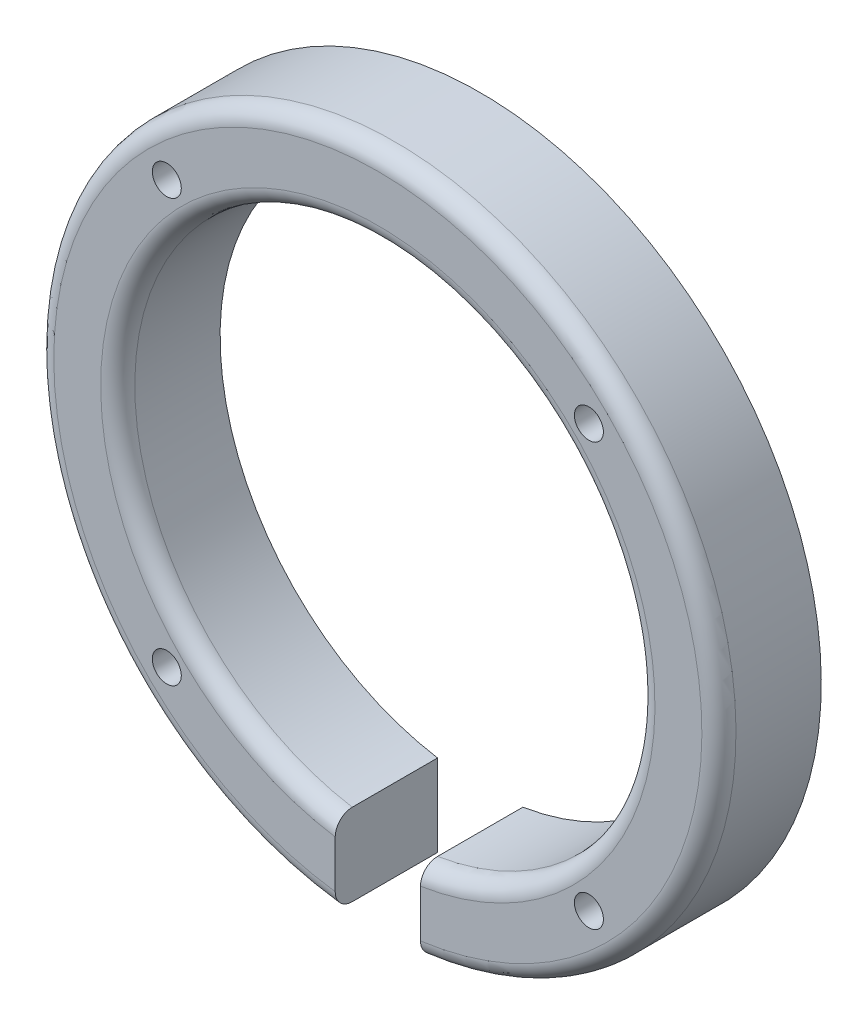
SolidWorks part; units mm, degrees
material "ABS"
ref_plane "前视基准面" through (0, 0, 0) normal (0, 0, 1) x (1, 0, 0)
ref_plane "上视基准面" through (0, 0, 0) normal (0, 1, 0) x (1, 0, 0)
ref_plane "右视基准面" through (0, 0, 0) normal (1, 0, 0) x (0, 0, -1)
sketch "草图1" plane through (0, 0, 0) normal (0, 0, 1) x (1, 0, 0)
  circle A0 centre (0, 0) radius 30.5
  circle A1 centre (0, 0) radius 40
  dimension "D1" = 61
  dimension "D2" = 80
extrude "凸台-拉伸1" add sketch "草图1" along normal blind 12
sketch "草图2" plane through (0, 0, 12) normal (0, 0, 1) x (1, 0, 0)
  line L0 (-28.2056, -28.2056) -> (28.3619, 28.3619) construction
  line L1 (0, 0) -> (0, 40) construction
  circle A1 centre (24.7487, 24.7487) radius 1.7
  circle A2 centre (24.7487, -24.7487) radius 1.7
  circle A3 centre (-24.7487, -24.7487) radius 1.7
  circle A4 centre (-24.7487, 24.7487) radius 1.7
  point P2 (26.6359, 22.7052)
  point P3 (0, 0)
  point P9 (0, 0)
  point P11 (24.5963, 24.9002)
  point P19 (0, 0)
  dimension "D2" = 3.4
  dimension "D1" = 35
  dimension "D4" = 35
  dimension "D5" = 45
  dimension "D3" = 4
extrude "切除-拉伸1" cut sketch "草图2" against normal blind 12
fillet "圆角1" radius 2 1 edges at (30.5, 0, 12)
fillet "圆角2" radius 2 1 edges at (40, 0, 12)
sketch "草图3" plane through (0, 0, 0) normal (0, 1, 0) x (1, 0, 0)
  line L0 (-5, 0) -> (5, 0)
  line L2 (40, 0) -> (-40, 0) construction
  line L3 (5, 0) -> (5, -17.1359)
  line L4 (5, -17.1359) -> (-5, -17.1359)
  line L6 (-5, 0) -> (-5, -17.1359)
  point P0 (-5, 0)
  dimension "D1" = 10
  dimension "D2" = 5
extrude "切除-拉伸2" cut sketch "草图3" along normal blind 10 and the other way through all
